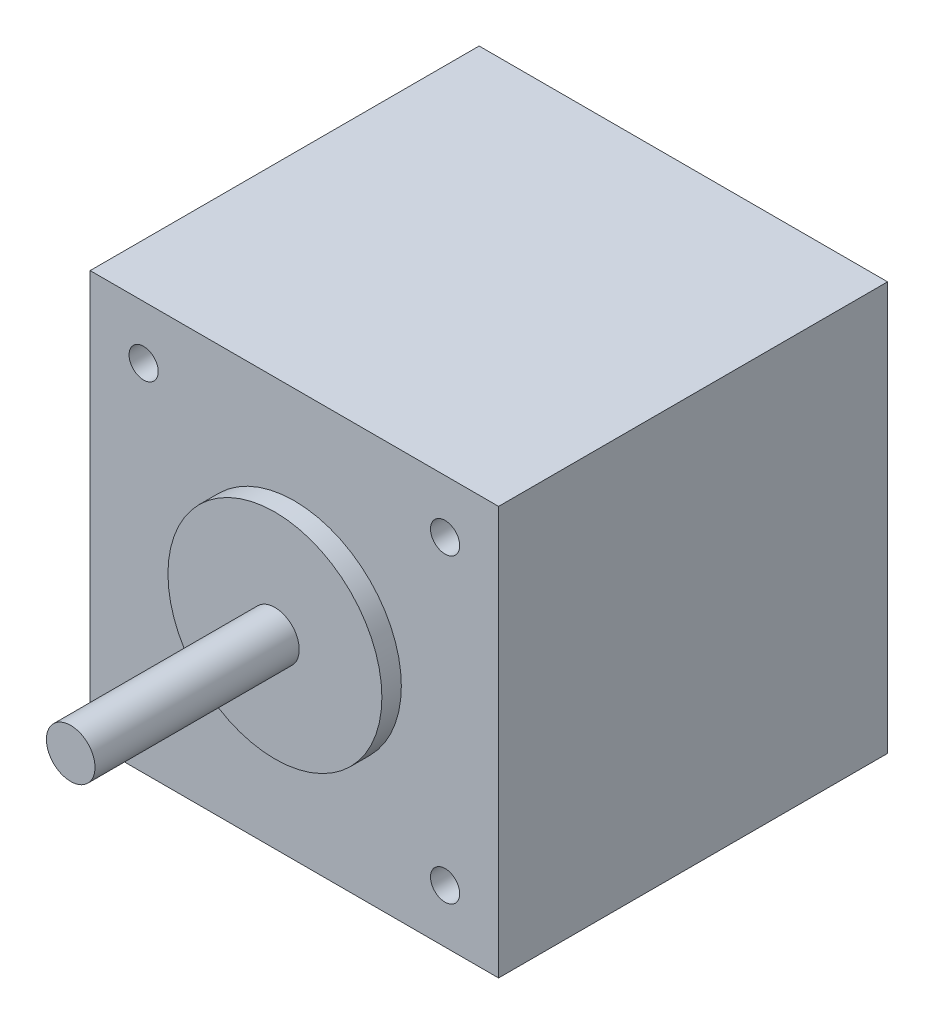
SolidWorks part; units mm, degrees
ref_plane "Спереди" through (0, 0, 0) normal (0, 0, 1) x (1, 0, 0)
ref_plane "Сверху" through (0, 0, 0) normal (0, 1, 0) x (1, 0, 0)
ref_plane "Справа" through (0, 0, 0) normal (1, 0, 0) x (0, 0, -1)
other "Configuration Table"
sketch "Эскиз1" plane through (0, 0, 0) normal (0, 0, 1) x (1, 0, 0)
  line L1 (-21, -21) -> (21, -21)
  line L2 (-21, -21) -> (-21, 21)
  line L3 (-21, 21) -> (21, 21)
  line L4 (21, -21) -> (21, 21)
  line L5 (-21, -21) -> (21, 21) construction
  line L6 (-21, 21) -> (21, -21) construction
  point P0 (0, 0)
  dimension "D1" = 42
  dimension "D2" = 42
extrude "Корпус" add sketch "Эскиз1" along normal blind 40
sketch "Эскиз2" plane through (0, 0, 0) normal (0, 0, 1) x (1, 0, 0)
  circle A0 centre (0, 0) radius 2.5
  dimension "D1" = 5
extrude "Вал_ПРЕДВ" add sketch "Эскиз2" along normal blind 63
sketch "Эскиз3" plane through (0, 0, 0) normal (0, 0, 1) x (1, 0, 0)
  circle A0 centre (0, 0) radius 11
  dimension "D1" = 22
extrude "Буртик_ПРЕДВ" add sketch "Эскиз3" along normal blind 42
sketch "Эскиз4" plane through (0, 0, 0) normal (0, 0, 1) x (1, 0, 0)
  circle A0 centre (-15.5, -15.5) radius 1.5
  circle A1 centre (-15.5, 15.5) radius 1.5
  circle A2 centre (15.5, -15.5) radius 1.5
  circle A3 centre (15.5, 15.5) radius 1.5
  dimension "D1" = 3
  dimension "D2" = 3
  dimension "D3" = 3
  dimension "D4" = 3
extrude "Крепеж_М3_ПРЕДВ" cut sketch "Эскиз4" against normal blind 4.5 from offset 40
equation "\"Мотор X ширина корпуса\"= 42.3"
equation "\"Мотор X высота корпуса\"= 42.3"
equation "\"Мотор X длина корпуса\"= 40"
equation "\"Мотор X вылет вала\"= 19.8"
equation "\"Мотор Y ширина корпуса\"= 42.3"
equation "\"Мотор Y высота корпуса\"= 42.3"
equation "\"Мотор Y длина корпуса\"= 48"
equation "\"Мотор Y вылет вала\"= 30"
equation "\"Мотор Z ширина корпуса\"= 42"
equation "\"Мотор Z высота корпуса\"= 42"
equation "\"Мотор Z длина корпуса\"= 40"
equation "\"Мотор Z вылет вала\"= 23"
equation "\"Мотор диаметр вала ПРЕДВ\"= 5"
equation "\"Мотор шаг крепления ПРЕДВ\"= 31"
equation "\"Мотор диаметр отверстий ПРЕДВ\"= 3"
equation "\"Мотор глубина отверстий ПРЕДВ\"= 4.5"
equation "\"Мотор диаметр буртика ПРЕДВ\"= 22"
equation "\"Мотор высота буртика ПРЕДВ\"= 2"
equation "\"Мотор диаметр шкива ПРЕДВ\"= 16"
equation "\"Мотор длина шкива ПРЕДВ\"= 12"
equation "\"Мотор отступ шкива ПРЕДВ\"= 5"
equation "\"Мотор X шаг градусов\"= 1.8"
equation "\"Мотор X ток А\"= 1.5"
equation "\"Мотор X сопротивление Ом\"= 1.3"
equation "\"Мотор X индуктивность мГн\"= 2"
equation "\"Мотор Y шаг градусов\"= 1.8"
equation "\"Мотор Y ток А\"= 2.2"
equation "\"Мотор Y сопротивление Ом\"= 0.9"
equation "\"Мотор Y индуктивность мГн\"= 2"
equation "\"Мотор Z шаг градусов\"= 1.8"
equation "\"Мотор Z ток А\"= 1"
equation "\"Мотор Z сопротивление Ом\"= 4"
equation "\"Мотор Z индуктивность мГн\"= 8"
equation "\"Мотор Y диаметр ротора\"= 25.78"
equation "\"D1@Эскиз1\" = \"Мотор Z ширина корпуса\""
equation "\"D2@Эскиз1\" = \"Мотор Z высота корпуса\""
equation "\"D1@Корпус\" = \"Мотор Z длина корпуса\""
equation "\"D1@Эскиз2\" = \"Мотор диаметр вала ПРЕДВ\""
equation "\"D1@Вал_ПРЕДВ\" = \"Мотор Z длина корпуса\" + \"Мотор Z вылет вала\""
equation "\"D1@Эскиз3\" = \"Мотор диаметр буртика ПРЕДВ\""
equation "\"D1@Буртик_ПРЕДВ\" = \"Мотор Z длина корпуса\" + \"Мотор высота буртика ПРЕДВ\""
equation "\"D1@Эскиз4\" = \"Мотор диаметр отверстий ПРЕДВ\""
equation "\"D2@Эскиз4\" = \"Мотор диаметр отверстий ПРЕДВ\""
equation "\"D3@Эскиз4\" = \"Мотор диаметр отверстий ПРЕДВ\""
equation "\"D4@Эскиз4\" = \"Мотор диаметр отверстий ПРЕДВ\""
equation "\"D1@Крепеж_М3_ПРЕДВ\" = \"Мотор глубина отверстий ПРЕДВ\""
equation "\"D19@Крепеж_М3_ПРЕДВ\" = \"Мотор Z длина корпуса\""
equation "\"Ширина груза\"= 160"
equation "\"Глубина груза\"= 240"
equation "\"Высота груза\"= 160"
equation "\"Ширина ячейки\"= \"Ширина груза\" + 10"
equation "\"Глубина ячейки\"= \"Глубина груза\" + 10"
equation "\"Высота ячейки\"= \"Высота груза\" + 10 + 13"
equation "\"Колво ячеек ширина\"= 2"
equation "\"Колво ячеек высота\"= 2"
equation "\"Толщина стенки\"= \"Толщина тонких панелей\""
equation "\"Крепление дверцы\"= 5 "
equation "\"Ширина рейки\"= \"Толщина шестерни\""
equation "\"Высота рейки\"= 20"
equation "\"Высота пола\"= 2*\"Толщина тонких панелей\""
equation "\"Колво полозьев\"= 5"
equation "\"Отступ рейки\"= 20"
equation "\"Глубина каретки\"= \"Глубина ячейки\" + 30 + \"Мотор Y высота корпуса\" + 20"
equation "\"Отступ шпильки\"= 26"
equation "\"Диаметр шпильки\"= 5"
equation "\"Длинна шпильки\"= (\"Высота ячейки\"+\"Толщина горизонтальных плит\"+\"Высота пола\")*\"Колво ячеек высота\"+2*(\"Толщина горизонтальных плит\"+\"Отступ рейки\")"
equation "\"Ширина пластины\"= 50  "
equation "\"Высота зона выгрузки\"= \"Высота ячейки\" * 2 + \"Толщина стенки\" * 2"
equation "\"Колво выгрузки\"= 1"
equation "\"Отступ крепления мотора фиксации\"= (\"Ширина пластины\"+20-\"Толщина вертикальных стенок\")/2"
equation "\"Диаметр оси\"= 10"
equation "\"Диаметр ролика\"= 20"
equation "\"Колво роликов\"= 10"
equation "\"Шаг роликов\"= \"Диаметр ролика\" + 20"
equation "\"Ширина ячейки выгрузки\"= \"Ширина ячейки\"+\"Толщина вертикальных стенок\"+2*\"Отступ крепления мотора фиксации\""
equation "\"Длинна рейки\"= (\"Ширина ячейки\"+\"Толщина вертикальных стенок\"+\"Крепление дверцы\")*\"Колво ячеек ширина\"+\"Ширина ячейки выгрузки\"*\"Колво выгрузки\"+\"Толщина вертикальных стенок\"+2*\"Отступ крепления мотора фиксации\"-\"Крепление дверцы\"*\"Колво ячеек ширина\""
equation "\"Толщина тонких панелей\"= 6"
equation "\"Толщина вертикальных стенок\"= 6"
equation "\"Толщина горизонтальных плит\"= 6"
equation "\"Базовая высота корпуса\"= (\"Высота ячейки\"+\"Толщина тонких панелей\"+\"Высота пола\")*\"Колво ячеек высота\"+6*\"Толщина тонких панелей\"+\"Мотор X ширина корпуса\"+\"Мотор Y ширина корпуса\"+75"
equation "\"Высота корпуса\"= (\"Высота ячейки\"+\"Толщина горизонтальных плит\"+\"Высота пола\")*\"Колво ячеек высота\"+2*\"Толщина горизонтальных плит\"+4*\"Толщина тонких панелей\"+\"Мотор X ширина корпуса\"+\"Мотор Y ширина корпуса\"+75"
equation "\"Смещение центра корпуса\"= (\"Высота корпуса\"-\"Базовая высота корпуса\")/2-(\"Толщина горизонтальных плит\"-\"Толщина тонких панелей\")"
equation "\"Отметка пола\"= -\"Базовая высота корпуса\"/2+\"Толщина тонких панелей\""
equation "\"Отметка потолка\"= \"Отметка пола\"+\"Высота корпуса\"-2*\"Толщина горизонтальных плит\""
equation "\"Отметка верхней полки\"= \"Отметка потолка\"-(28+\"Толщина тонких панелей\")-\"Высота ячейки\"-\"Высота пола\""
equation "\"Отметка нижней полки\"= \"Отметка верхней полки\"-\"Высота ячейки\"-\"Высота пола\"-\"Толщина горизонтальных плит\""
equation "\"Толщина шестерни\"= 10"
